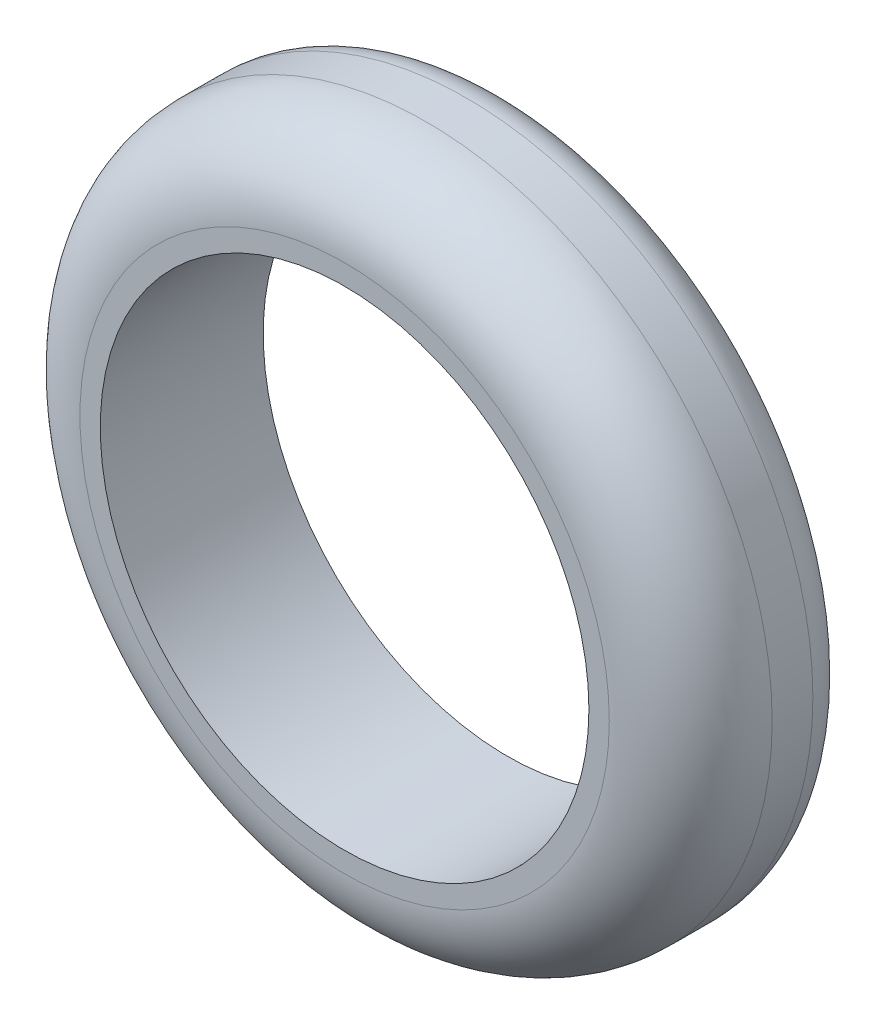
SolidWorks part; units mm, degrees
material "NEOPRENE"
ref_plane "Front Plane" through (0, 0, 0) normal (0, 0, 1) x (1, 0, 0)
ref_plane "Top Plane" through (0, 0, 0) normal (0, 1, 0) x (1, 0, 0)
ref_plane "Right Plane" through (0, 0, 0) normal (1, 0, 0) x (0, 0, -1)
sketch "Sketch1" plane through (0, 0, 0) normal (0, 0, 1) x (1, 0, 0)
  circle A0 centre (0, 0) radius 4.25
  circle A1 centre (0, 0) radius 3
  dimension "D1" = 6
  dimension "D2" = 8.5
extrude "Boss-Extrude2" add sketch "Sketch1" along normal blind 2 contours A0 A1
fillet "Fillet3" radius 1 1 edges at (4.25, 0, 2)
fillet "Fillet4" radius 0.5 1 edges at (4.25, 0, 0)
